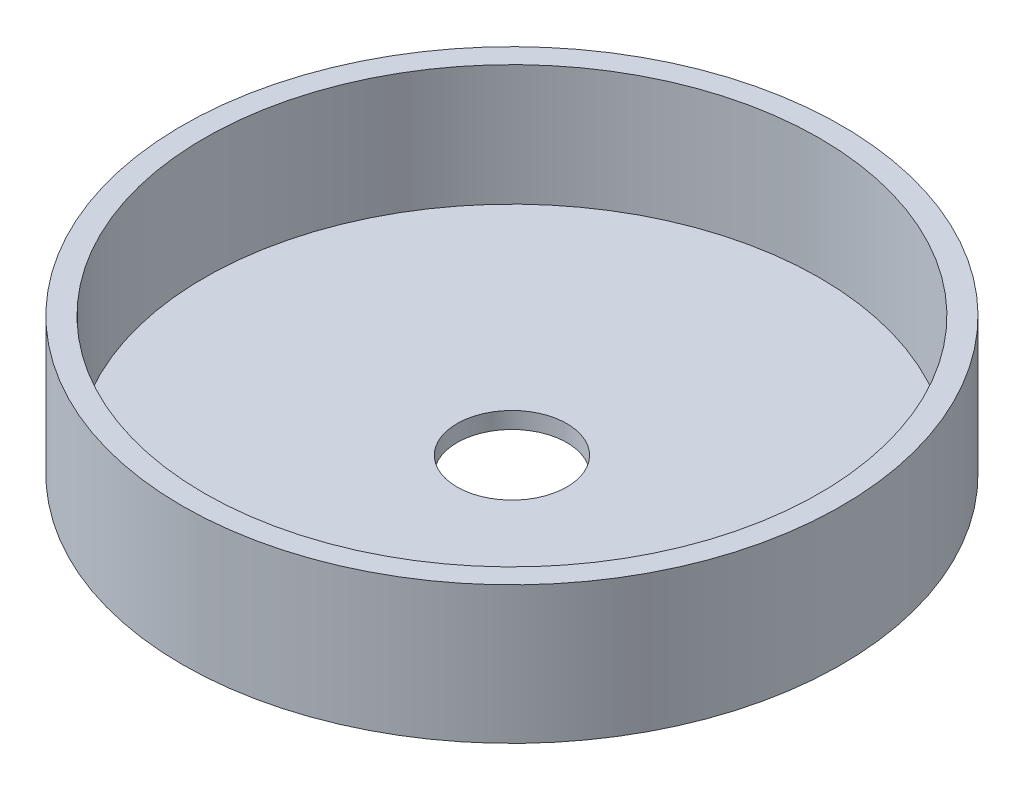
SolidWorks part; units mm, degrees
ref_plane "Front Plane" through (0, 0, 0) normal (0, 0, 1) x (1, 0, 0)
ref_plane "Top Plane" through (0, 0, 0) normal (0, 1, 0) x (1, 0, 0)
ref_plane "Right Plane" through (0, 0, 0) normal (1, 0, 0) x (0, 0, -1)
sketch "Puck Base Sketch" plane through (0, 0, 0) normal (0, 1, 0) x (1, 0, 0)
  circle A0 centre (0, 0) radius 60
  circle A1 centre (0, 0) radius 10
  dimension "D1" = 120
  dimension "D2" = 20
extrude "Puck Base" add sketch "Puck Base Sketch" along normal blind 3
sketch "Puck Wall Sketch" plane through (0, 0, 0) normal (0, 1, 0) x (1, 0, 0)
  circle A0 centre (0, 0) radius 60
  circle A1 centre (0, 0) radius 56
  dimension "D1" = 120
  dimension "D2" = 112
extrude "Puck Wall" add sketch "Puck Wall Sketch" along normal blind 25
